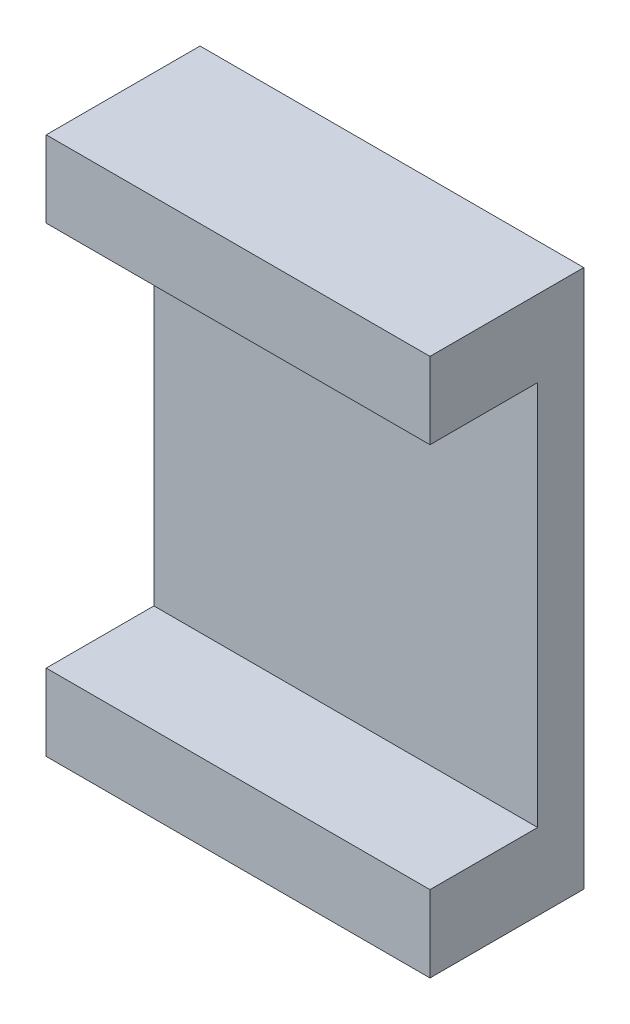
SolidWorks part; units mm, degrees
ref_plane "Front Plane" through (0, 0, 0) normal (0, 0, 1) x (1, 0, 0)
ref_plane "Top Plane" through (0, 0, 0) normal (0, 1, 0) x (1, 0, 0)
ref_plane "Right Plane" through (0, 0, 0) normal (1, 0, 0) x (0, 0, -1)
sketch "Sketch1" plane through (0, 0, 0) normal (0, 0, 1) x (1, 0, 0)
  line L1 (-12.475, -17.5) -> (12.475, -17.5)
  line L2 (-12.475, -17.5) -> (-12.475, 17.5)
  line L3 (-12.475, 17.5) -> (12.475, 17.5)
  line L4 (12.475, -17.5) -> (12.475, 17.5)
  line L5 (-12.475, -17.5) -> (12.475, 17.5) construction
  line L6 (-12.475, 17.5) -> (12.475, -17.5) construction
  point P0 (0, 0)
  dimension "D1" = 24.95
  dimension "D2" = 35
extrude "Boss-Extrude1" add sketch "Sketch1" along normal blind 10
sketch "Sketch2" plane through (0, 0, 10) normal (0, 0, 1) x (1, 0, 0)
  line L0 (12.475, -17.5) -> (12.475, 17.5) construction
  line L1 (-12.475, -12.525) -> (12.475, -12.525)
  line L2 (-12.475, -12.525) -> (-12.475, 12.525)
  line L3 (-12.475, 12.525) -> (12.475, 12.525)
  line L4 (12.475, -12.525) -> (12.475, 12.525)
  line L5 (-12.475, -12.525) -> (12.475, 12.525) construction
  line L6 (-12.475, 12.525) -> (12.475, -12.525) construction
  point P0 (0, 0)
  dimension "D1" = 25.05
extrude "Cut-Extrude1" cut sketch "Sketch2" against normal blind 7
